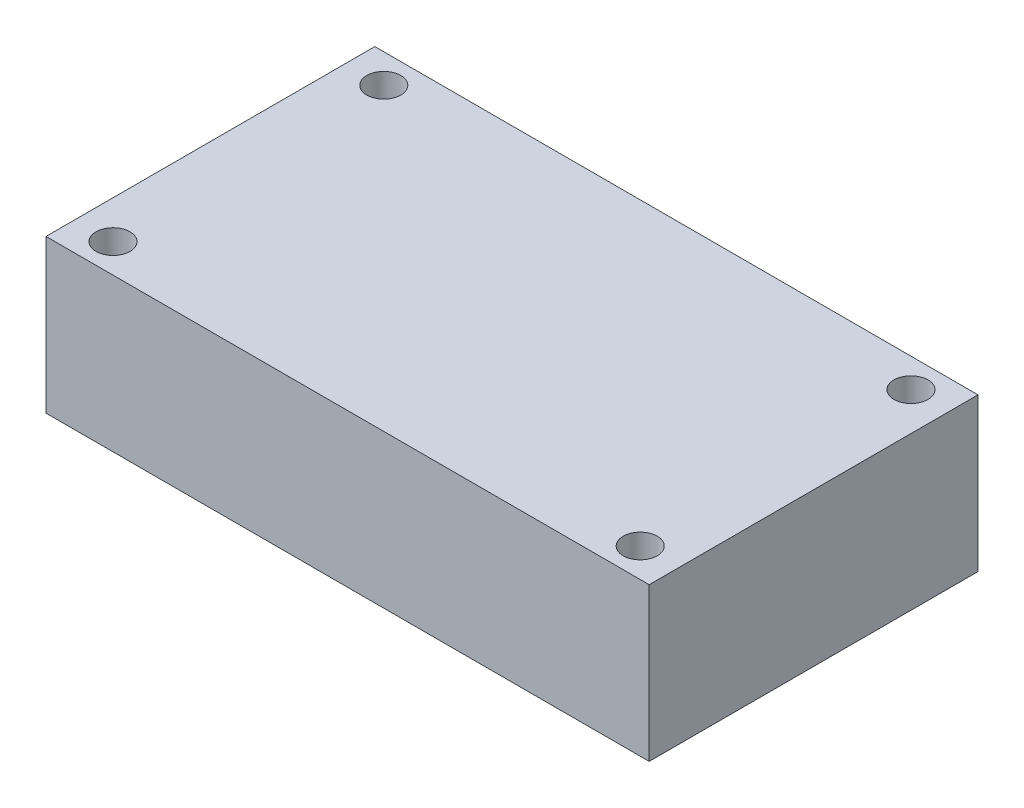
SolidWorks part; units mm, degrees
ref_plane "Спереди" through (0, 0, 0) normal (0, 0, 1) x (1, 0, 0)
ref_plane "Сверху" through (0, 0, 0) normal (0, 1, 0) x (1, 0, 0)
ref_plane "Справа" through (0, 0, 0) normal (1, 0, 0) x (0, 0, -1)
other "Configuration Table"
sketch "Эскиз1" plane through (0, 0, 0) normal (0, 1, 0) x (1, 0, 0)
  line L1 (26.6, -14.5) -> (-26.6, -14.5)
  line L2 (26.6, -14.5) -> (26.6, 14.5)
  line L3 (26.6, 14.5) -> (-26.6, 14.5)
  line L4 (-26.6, -14.5) -> (-26.6, 14.5)
  line L5 (26.6, -14.5) -> (-26.6, 14.5) construction
  line L6 (26.6, 14.5) -> (-26.6, -14.5) construction
  point P0 (0, 0)
extrude "Бобышка-Вытянуть1" add sketch "Эскиз1" along normal blind 13.5
sketch "Эскиз2" plane through (0, 0, 0) normal (0, -1, 0) x (1, 0, 0)
  circle A0 centre (-23.25, 11.94) radius 1.5
  circle A1 centre (23.25, 11.94) radius 1.5
  circle A2 centre (23.25, -11.94) radius 1.5
  circle A3 centre (-23.25, -11.94) radius 1.5
  point P10 (0, 0)
extrude "Вырез-Вытянуть1" cut sketch "Эскиз2" against normal blind 50
